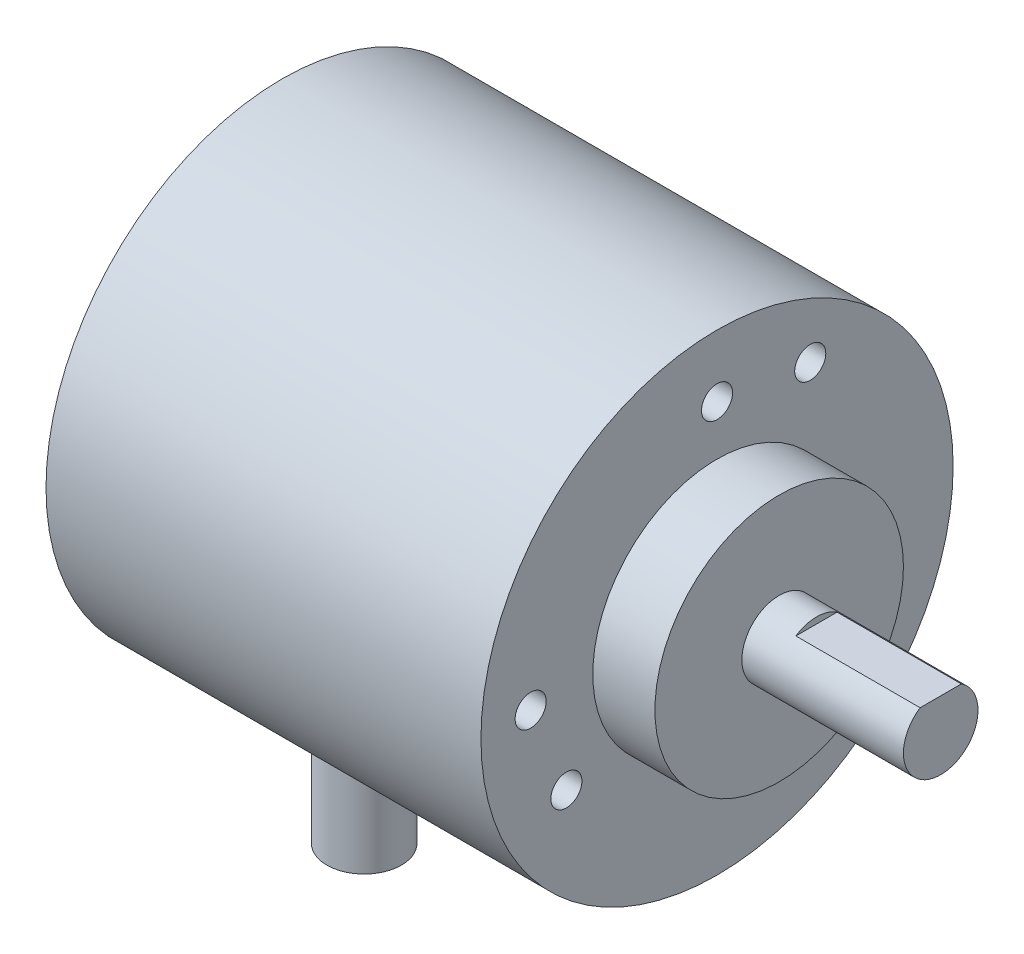
SolidWorks part; units mm, degrees
ref_plane "Front Plane" through (0, 0, 0) normal (0, 0, 1) x (1, 0, 0)
ref_plane "Top Plane" through (0, 0, 0) normal (0, 1, 0) x (1, 0, 0)
ref_plane "Right Plane" through (0, 0, 0) normal (1, 0, 0) x (0, 0, -1)
sketch "Sketch1" plane through (0, 0, 0) normal (1, 0, 0) x (0, 0, -1)
  circle A0 centre (0, 0) radius 19
extrude "Boss-Extrude1" add sketch "Sketch1" along normal blind 35
sketch "Sketch2" plane through (35, 0, 0) normal (1, 0, 0) x (0, 0, -1)
  circle A0 centre (0, 0) radius 10
extrude "Boss-Extrude2" add sketch "Sketch2" along normal blind 5 contours A0
sketch "Sketch3" plane through (40, 0, 0) normal (1, 0, 0) x (0, 0, -1)
  circle A0 centre (0, 0) radius 3
extrude "Boss-Extrude3" add sketch "Sketch3" along normal blind 13
sketch "Sketch4" plane through (53, 0, 0) normal (1, 0, 0) x (0, 0, -1)
  line L0 (55, 0) -> (-55, 0) construction
  line L1 (-5.481, 5.8181) -> (5.3887, 5.8181)
  line L2 (-5.481, 5.8181) -> (-5.481, 2.5)
  line L3 (-5.481, 2.5) -> (5.3887, 2.5)
  line L4 (5.3887, 5.8181) -> (5.3887, 2.5)
  dimension "D1" = 2.5
extrude "Cut-Extrude1" cut sketch "Sketch4" against normal blind 10
ref_plane "Plane1" through (0, -19, 0) normal (0, -1, 0) x (-1, 0, 0)
sketch "Sketch5" plane through (0, -19, 0) normal (0, -1, 0) x (-1, 0, 0)
  line L1 (-44.2539, 0) -> (44.2539, 0) construction
  circle A0 centre (-6.6045, 0) radius 5
extrude "Boss-Extrude4" add sketch "Sketch5" along normal blind 2 and the other way up to surface other way up to face at (35, 0, -19)
sketch "Sketch6" plane through (0, -21, 0) normal (0, -1, 0) x (1, 0, 0)
  circle A0 centre (6.6045, 0) radius 3
extrude "Boss-Extrude5" add sketch "Sketch6" along normal blind 10
hole_wizard "M3 Tapped Hole1" positions "Sketch9" profile "Sketch10" tap size "M3" standard "ISO"
sketch "Sketch9" plane through (35, 0, 0) normal (-1, 0, 0) x (0, 0, 1)
  line L0 (0, -44.2539) -> (0, 44.2539) construction
  line L1 (55, 0) -> (-55, 0) construction
  point P0 (-7.5, 12.9904)
  point P6 (0, 14)
  dimension "D1" = 15
  dimension "D2" = 7.5
  dimension "D3" = 14
sketch "Sketch10" plane through (35, 12.9904, -7.5) normal (0, 1, 0) x (0, 0, -1)
  line L0 (0, 0) -> (0, 8.2511)
  line L1 (0, 8.2511) -> (1.25, 7.5)
  line L2 (1.25, 7.5) -> (1.25, 0)
  line L5 (1.25, 0) -> (0, 0)
  line L10 (0, 8.2511) -> (-1.25, 7.5) construction
  line L11 (0, -6.35) -> (0, 107.95) construction
  dimension "Tap Drill Dia." = 2.5
  dimension "Tap Drill Depth" = 7.5
  dimension "Drill Angle" = 118
cosmetic thread "Hole Thread1" parameters "D1"=6, "D2"=3
cosmetic thread "Hole Thread2" parameters "D1"=6, "D2"=3
pattern_circular "CirPattern1" count 3 over 360 about axis through (0, 0, 0) along (1, 0, 0) of "M3 Tapped Hole1"
equation "\"D2@Sketch9\"=15*sin(30)"
